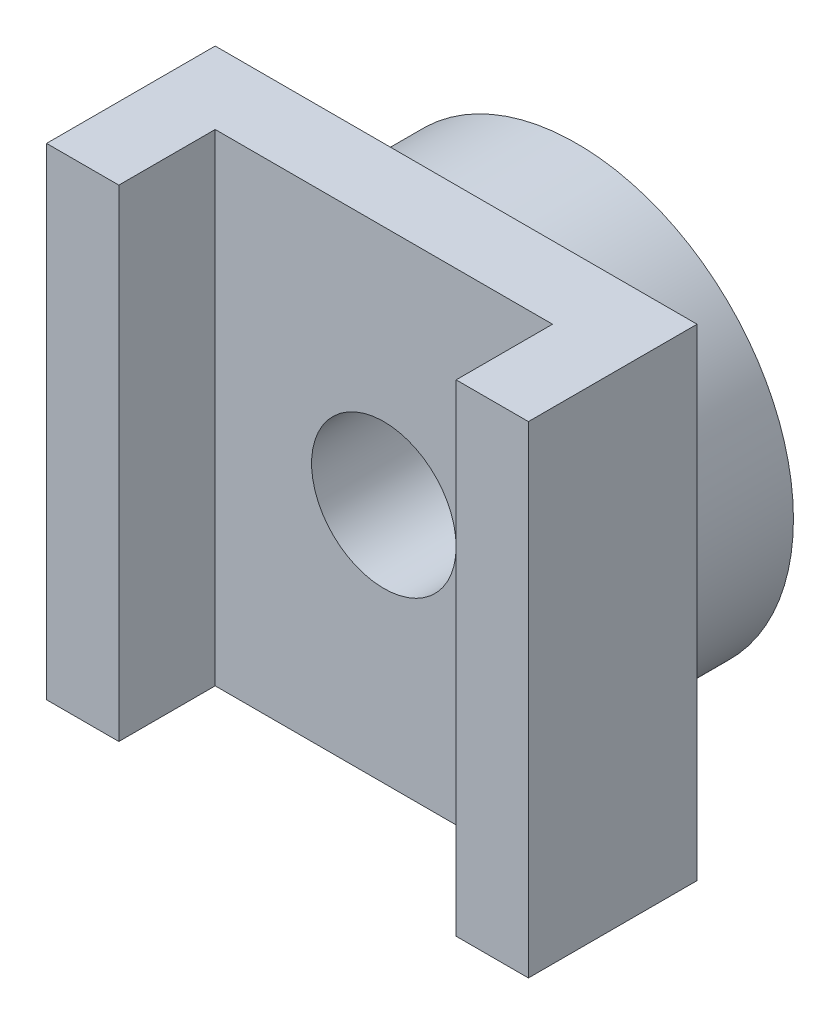
SolidWorks part; units mm, degrees
ref_plane "前基準面" through (0, 0, 0) normal (0, 0, 1) x (1, 0, 0)
ref_plane "上基準面" through (0, 0, 0) normal (0, 1, 0) x (1, 0, 0)
ref_plane "右基準面" through (0, 0, 0) normal (1, 0, 0) x (0, 0, -1)
sketch "草圖1" plane through (0, 0, 0) normal (0, 0, 1) x (1, 0, 0)
  circle A0 centre (0, 0) radius 4.5
  dimension "D1" = 9
extrude "填料-伸長1" add sketch "草圖1" along normal blind 2.5
sketch "草圖2" plane through (0, 0, 2.5) normal (0, 0, 1) x (1, 0, 0)
  line L1 (-5, -5) -> (5, -5)
  line L2 (-5, -5) -> (-5, 5)
  line L3 (-5, 5) -> (5, 5)
  line L4 (5, -5) -> (5, 5)
  line L5 (-5, -5) -> (5, 5) construction
  line L6 (-5, 5) -> (5, -5) construction
  point P0 (0, 0)
  dimension "D1" = 10
extrude "填料-伸長2" add sketch "草圖2" along normal blind 1.5
sketch "草圖3" plane through (0, 0, 4) normal (0, 0, 1) x (1, 0, 0)
  line L0 (-5, -5) -> (5, -5) construction
  line L1 (-5, 5) -> (-3.5, 5)
  line L2 (-5, 5) -> (-5, -5)
  line L3 (-5, -5) -> (-3.5, -5)
  line L4 (-3.5, 5) -> (-3.5, -5)
  dimension "D1" = 1.5
extrude "填料-伸長3" add sketch "草圖3" along normal blind 2
mirror "鏡射1" about plane through (0, 0, 0) normal (1, 0, 0) of "填料-伸長3"
hole_wizard "Ø3.0 (3) 直徑孔1" positions "草圖4" profile "草圖5" hole size "Ø3.0" standard "ISO" end condition through all
sketch "草圖4" plane through (0, 0, 4) normal (0, 0, 1) x (1, 0, 0)
  point P0 (0, 0)
sketch "草圖5" plane through (0, 0, 4) normal (1, 0, 0) x (0, -1, 0)
  line L0 (0, 0) -> (0, 4)
  line L1 (0, 4) -> (1.5, 4)
  line L2 (1.5, 4) -> (1.5, 0)
  line L5 (1.5, 0) -> (0, 0)
  line L11 (0, -6.35) -> (0, 107.95) construction
  dimension "貫穿孔直徑" = 3
  dimension "貫穿孔深度" = 4
